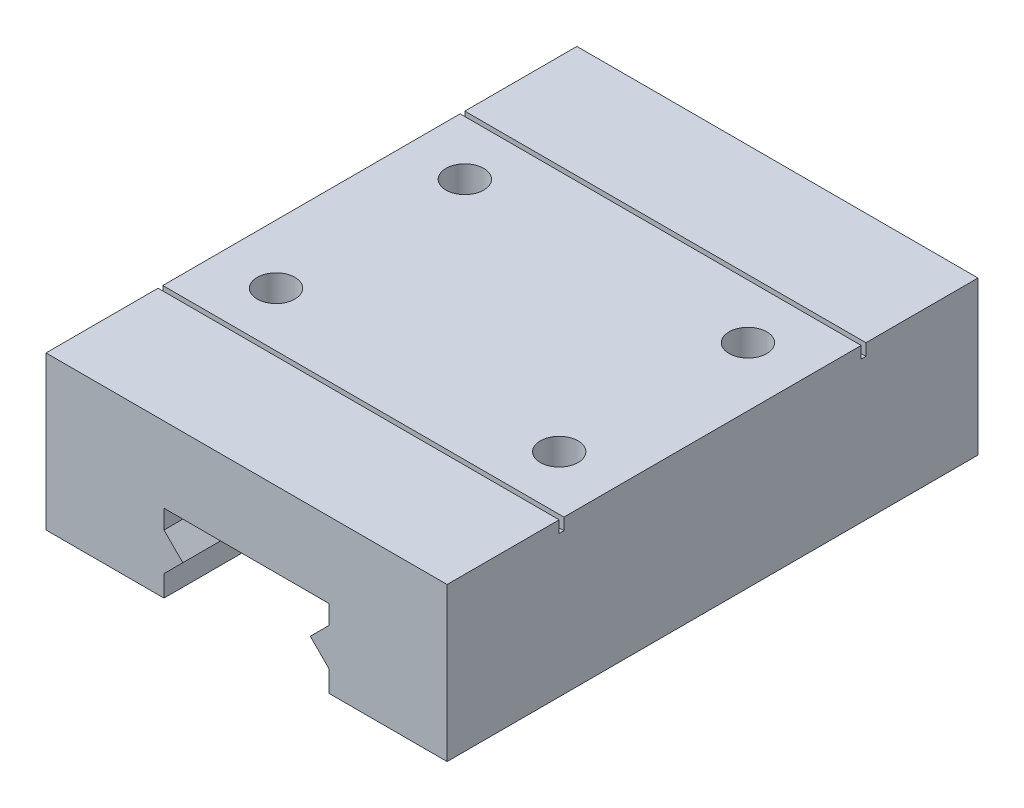
SolidWorks part; units mm, degrees
material "合金钢"
ref_plane "前视基准面" through (0, 0, 0) normal (0, 0, 1) x (1, 0, 0)
ref_plane "上视基准面" through (0, 0, 0) normal (0, 1, 0) x (1, 0, 0)
ref_plane "右视基准面" through (0, 0, 0) normal (1, 0, 0) x (0, 0, -1)
sketch "草图2" plane through (0, 0, 0) normal (0, 0, 1) x (1, 0, 0)
  line L0 (0, 0) -> (0, -6.5) construction
  line L1 (-8.5, 0) -> (8.5, 0)
  line L2 (8.5, 0) -> (8.5, -6.5)
  line L3 (8.5, -6.5) -> (3.5, -6.5)
  line L4 (3.5, -6.5) -> (3.5, -5.6)
  line L5 (3.5, -5.6) -> (2.7, -4.8)
  line L6 (2.7, -4.8) -> (3.5, -4)
  line L7 (3.5, -4) -> (3.5, -3.2)
  line L8 (3.5, -3.2) -> (-3.5, -3.2)
  line L9 (-3.5, -4) -> (-3.5, -3.2)
  line L10 (-2.7, -4.8) -> (-3.5, -4)
  line L11 (-3.5, -5.6) -> (-2.7, -4.8)
  line L12 (-3.5, -6.5) -> (-3.5, -5.6)
  line L13 (-8.5, -6.5) -> (-3.5, -6.5)
  line L14 (-8.5, 0) -> (-8.5, -6.5)
  point P14 (0, -3.2)
  dimension "D1" = 6.5
  dimension "D2" = 8.5
  dimension "D3" = 3.5
  dimension "D4" = 45
  dimension "D5" = 0.8
  dimension "D6" = 0.8
  dimension "D7" = 3.3
extrude "凸台-拉伸1" add sketch "草图2" along normal blind 22.5
sketch "草图3" plane through (0, 0, 0) normal (0, 1, 0) x (1, 0, 0)
  line L0 (-8.5, -11.25) -> (8.5, -11.25) construction
  line L1 (-8.5, -22.5) -> (-8.5, 0) construction
  line L2 (8.5, -22.5) -> (8.5, 0) construction
  line L3 (8.5, -17.75) -> (8.5, -17.55)
  line L4 (-8.5, -4.75) -> (8.5, -4.75)
  line L5 (-8.5, -4.75) -> (-8.5, -4.95)
  line L6 (-8.5, -4.95) -> (8.5, -4.95)
  line L7 (8.5, -4.75) -> (8.5, -4.95)
  line L8 (-8.5, -17.55) -> (8.5, -17.55)
  line L9 (-8.5, -17.75) -> (-8.5, -17.55)
  line L10 (-8.5, -17.75) -> (8.5, -17.75)
  dimension "D1" = 0.2
  dimension "D2" = 6.5
extrude "切除-拉伸1" cut sketch "草图3" against normal blind 0.5
hole_wizard "M2 螺纹孔1" positions "草图4" profile "草图5" tap size "M2" standard "GB"
sketch "草图4" plane through (0, 0, 0) normal (0, 1, 0) x (1, 0, 0)
  line L1 (-6, -7.25) -> (6, -7.25)
  line L2 (-6, -7.25) -> (-6, -15.25)
  line L3 (-6, -15.25) -> (6, -15.25)
  line L4 (6, -7.25) -> (6, -15.25)
  line L5 (-8.5, -17.55) -> (-8.5, -4.95) construction
  point P0 (-6, -7.25)
  point P2 (6, -7.25)
  point P4 (6, -15.25)
  point P6 (-6, -15.25)
  point P48 (0, -7.25)
  point P50 (-6, -11.25)
  point P53 (-8.5, -11.25)
  dimension "D1" = 12
  dimension "D2" = 8
sketch "草图5" plane through (-6, 0, 7.25) normal (1, 0, 0) x (0, 0, 1)
  line L0 (0, 0) -> (0, 4.6807)
  line L1 (0, 4.6807) -> (0.8, 4.2)
  line L2 (0.8, 4.2) -> (0.8, 0)
  line L5 (0.8, 0) -> (0, 0)
  line L10 (0, 4.6807) -> (-0.8, 4.2) construction
  line L11 (0, -6.35) -> (0, 107.95) construction
  dimension "螺纹孔钻头直径" = 1.6
  dimension "螺纹孔钻头深度" = 4.2
  dimension "导头角度" = 118
cosmetic thread "孔螺蚊线1" parameters "D1"=3, "D2"=2
cosmetic thread "孔螺蚊线2" parameters "D1"=3, "D2"=2
cosmetic thread "孔螺蚊线3" parameters "D1"=3, "D2"=2
cosmetic thread "孔螺蚊线4" parameters "D1"=3, "D2"=2
